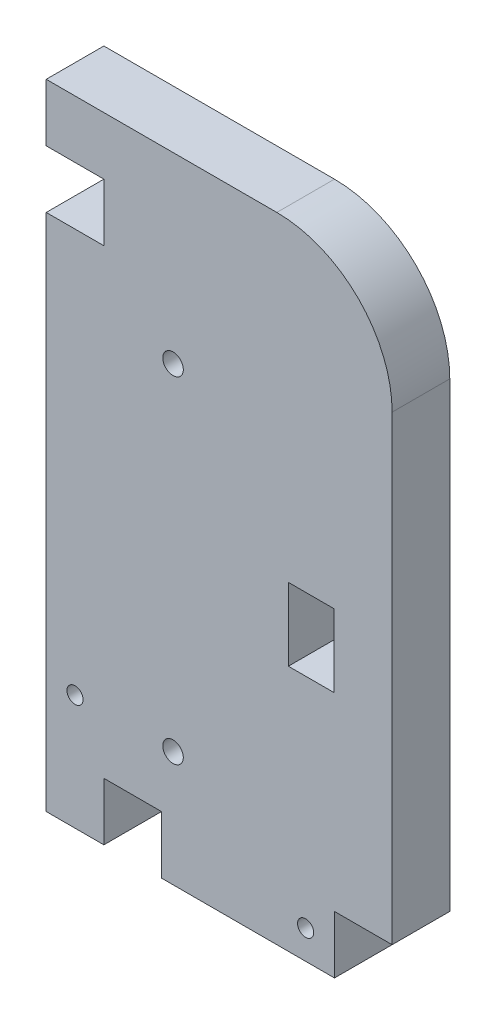
SolidWorks part; units mm, degrees
ref_plane "Front Plane" through (0, 0, 0) normal (0, 0, 1) x (1, 0, 0)
ref_plane "Top Plane" through (0, 0, 0) normal (0, 1, 0) x (1, 0, 0)
ref_plane "Right Plane" through (0, 0, 0) normal (1, 0, 0) x (0, 0, -1)
sketch "Sketch1" plane through (0, 0, 0) normal (0, 0, 1) x (1, 0, 0)
  line L0 (-16.1345, 9.3173) -> (-16.1345, -47.8327)
  line L1 (-16.1345, 22.0173) -> (9.2655, 22.0173)
  line L2 (-16.1345, 22.0173) -> (-16.1345, 15.6673)
  line L3 (-3.4345, -47.8327) -> (15.6155, -47.8327)
  line L4 (21.9655, 9.3173) -> (21.9655, -41.4827)
  line L5 (-16.1345, 15.6673) -> (-9.7845, 15.6673)
  line L7 (-16.1345, 9.3173) -> (-9.7845, 9.3173)
  line L8 (-9.7845, 15.6673) -> (-9.7845, 9.3173)
  line L9 (10.5355, -12.6327) -> (15.5355, -12.6327)
  line L10 (10.5355, -12.6327) -> (10.5355, -20.6327)
  line L11 (10.5355, -20.6327) -> (15.5355, -20.6327)
  line L12 (15.5355, -12.6327) -> (15.5355, -20.6327)
  line L13 (-9.7845, -47.8327) -> (-9.7845, -41.4827)
  line L14 (-9.7845, -41.4827) -> (-3.4345, -41.4827)
  line L15 (-16.1345, -47.8327) -> (-9.7845, -47.8327)
  line L16 (-3.4345, -47.8327) -> (-3.4345, -41.4827)
  line L19 (21.9655, -41.4827) -> (15.6155, -41.4827)
  line L20 (15.6155, -47.8327) -> (15.6155, -41.4827)
  circle A0 centre (-2.1645, -35.1327) radius 1.1303
  circle A1 centre (-2.1645, 1.8673) radius 1.1303
  circle A2 centre (12.4405, -44.6577) radius 0.889
  circle A3 centre (-12.9595, -35.1327) radius 0.889
  arc A4 (9.2655, 22.0173) -> (21.9655, 9.3173) centre (9.2655, 9.3173) cw
  dimension "D5" = 2.2606
  dimension "D6" = 2.2606
  dimension "D7" = 37
  dimension "D8" = 12.7
  dimension "D10" = 7.62
  dimension "D11" = 0
  dimension "D12" = 14.5
  dimension "D21" = 3.175
  dimension "D22" = 3.175
  dimension "D23" = 1.778
  dimension "D24" = 12.7
  dimension "D25" = 1.778
  dimension "D9" = 12.7
  dimension "D1" = 6.35
  dimension "D2" = 6.35
  dimension "D3" = 6.35
  dimension "D4" = 57.15
  dimension "D13" = 8
  dimension "D14" = 12.7
  dimension "D15" = 5
  dimension "D16" = 6.35
  dimension "D17" = 6.35
  dimension "D18" = 6.35
  dimension "D19" = 6.35
  dimension "D20" = 6.35
extrude "Boss-Extrude1" add sketch "Sketch1" along normal blind 6.35
